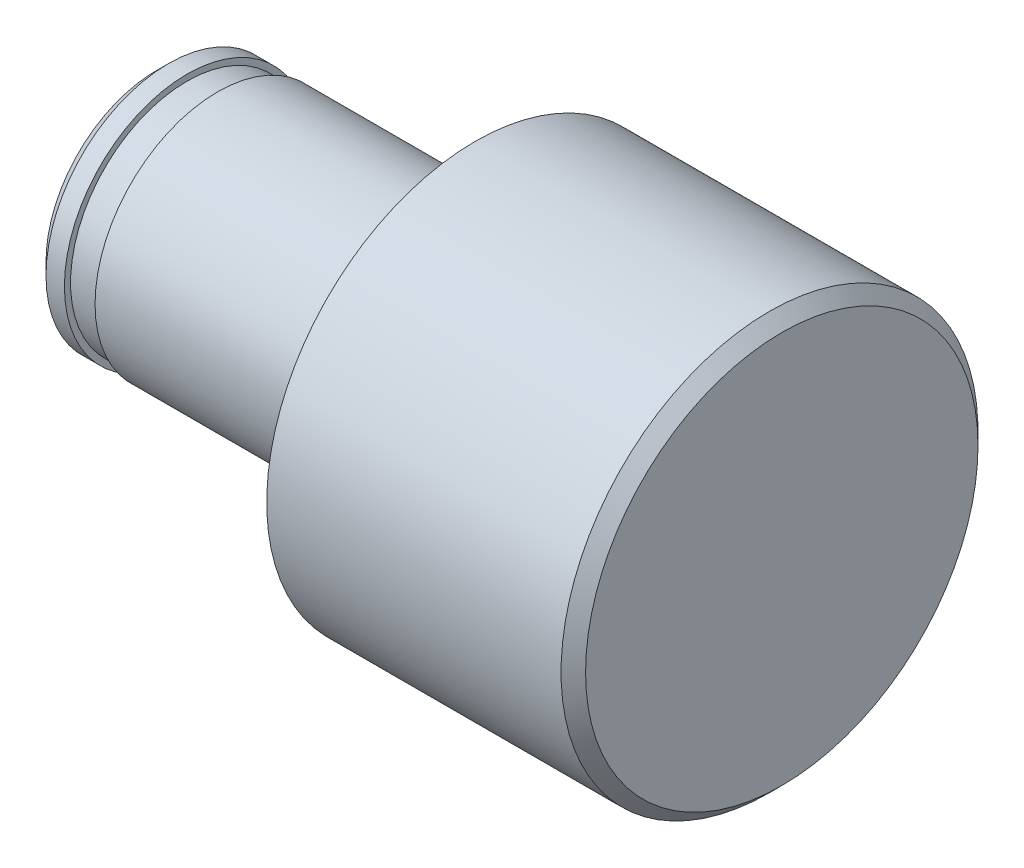
SolidWorks part; units mm, degrees
ref_plane "Vorne" through (0, 0, 0) normal (0, 0, 1) x (1, 0, 0)
ref_plane "Oben" through (0, 0, 0) normal (0, 1, 0) x (1, 0, 0)
ref_plane "Seite" through (0, 0, 0) normal (1, 0, 0) x (0, 0, -1)
sketch "Skizze2" plane through (0, 0, 0) normal (0, 0, 1) x (1, 0, 0)
  line L0 (3.9565, 0) -> (-6.2435, 0)
  line L1 (-6.2435, 0) -> (-6.2435, 2)
  line L2 (-6.2435, 2) -> (-5.7435, 2)
  line L3 (-5.7435, 2) -> (-5.7435, 1.9)
  line L4 (-5.7435, 1.9) -> (-5.2435, 1.9)
  line L5 (-5.2435, 1.9) -> (-5.2435, 2)
  line L6 (-5.2435, 2) -> (-1.0435, 2)
  line L7 (-1.0435, 2) -> (-1.0435, 3.4)
  line L8 (-1.0435, 3.4) -> (3.9565, 3.4)
  line L9 (3.9565, 3.4) -> (3.9565, 0)
  dimension "D1" = 0.5
  dimension "D2" = 0.1
  dimension "D3" = 0.5
  dimension "D4" = 4.2
  dimension "D5" = 5
  dimension "D6" = 3.4
  dimension "D7" = 2
revolve "Rotation1" add sketch "Skizze2" angle 360 about L0
chamfer "Fase1" distance 0.2 angle 45 2 edges at (3.9565, 3.4, 0) (-6.2435, 2, 0)
